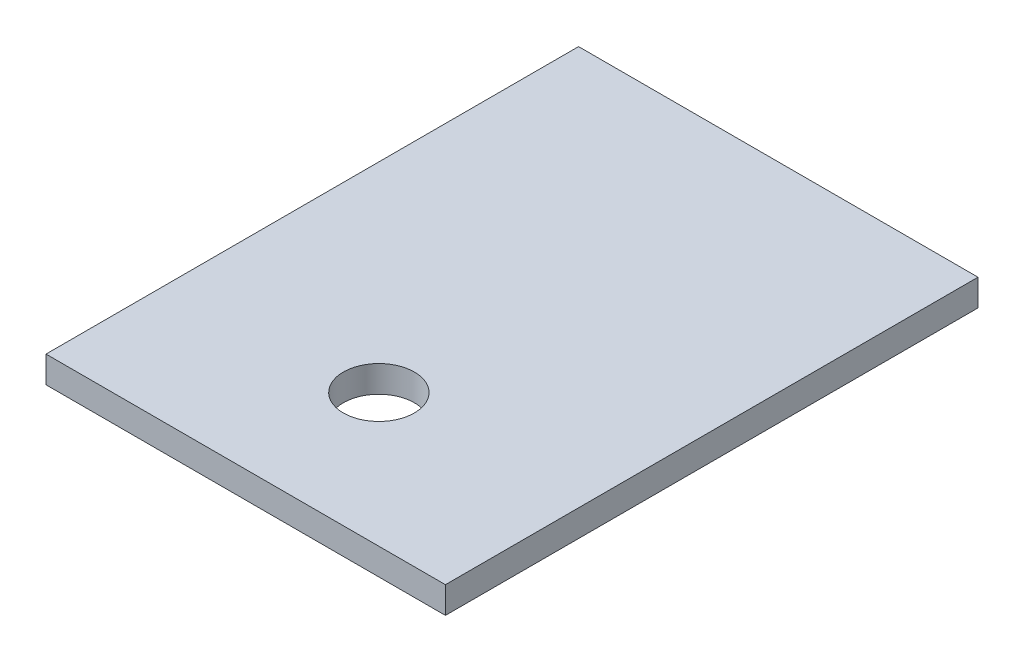
SolidWorks part; units mm, degrees
ref_plane "Front Plane" through (0, 0, 0) normal (0, 0, 1) x (1, 0, 0)
ref_plane "Top Plane" through (0, 0, 0) normal (0, 1, 0) x (1, 0, 0)
ref_plane "Right Plane" through (0, 0, 0) normal (1, 0, 0) x (0, 0, -1)
sketch "Sketch1" plane through (0, 0, 0) normal (0, 1, 0) x (1, 0, 0)
  line L1 (0, 0) -> (45, 0)
  line L2 (0, 0) -> (0, 60)
  line L3 (0, 60) -> (45, 60)
  line L4 (45, 0) -> (45, 60)
  circle A0 centre (22.5, 15) radius 4
  dimension "D2" = 8
  dimension "D1" = 45
  dimension "D3" = 22.5
  dimension "D4" = 15
  dimension "D5" = 60
extrude "Boss-Extrude1" add sketch "Sketch1" along normal blind 3
